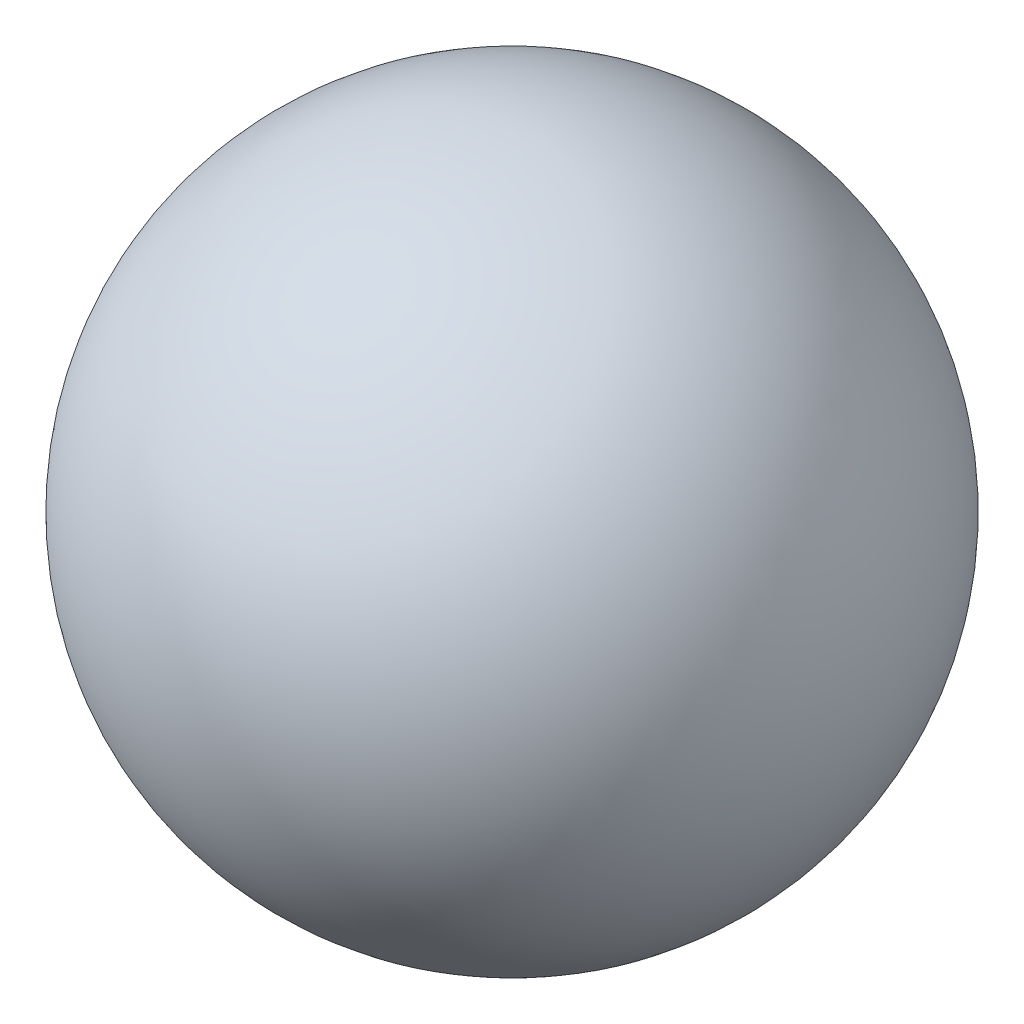
SolidWorks part; units mm, degrees
ref_plane "Front Plane" through (0, 0, 0) normal (0, 0, 1) x (1, 0, 0)
ref_plane "Top Plane" through (0, 0, 0) normal (0, 1, 0) x (1, 0, 0)
ref_plane "Right Plane" through (0, 0, 0) normal (1, 0, 0) x (0, 0, -1)
sketch "Sketch1" plane through (0, 0, 0) normal (0, 0, 1) x (1, 0, 0)
  line L4 (0, 6.35) -> (0, -6.35)
  arc A2 (0, -6.35) -> (0, 6.35) centre (0, 0) ccw
  dimension "D1" = 12.7
revolve "Revolve1" add sketch "Sketch1" angle 360 about L4
